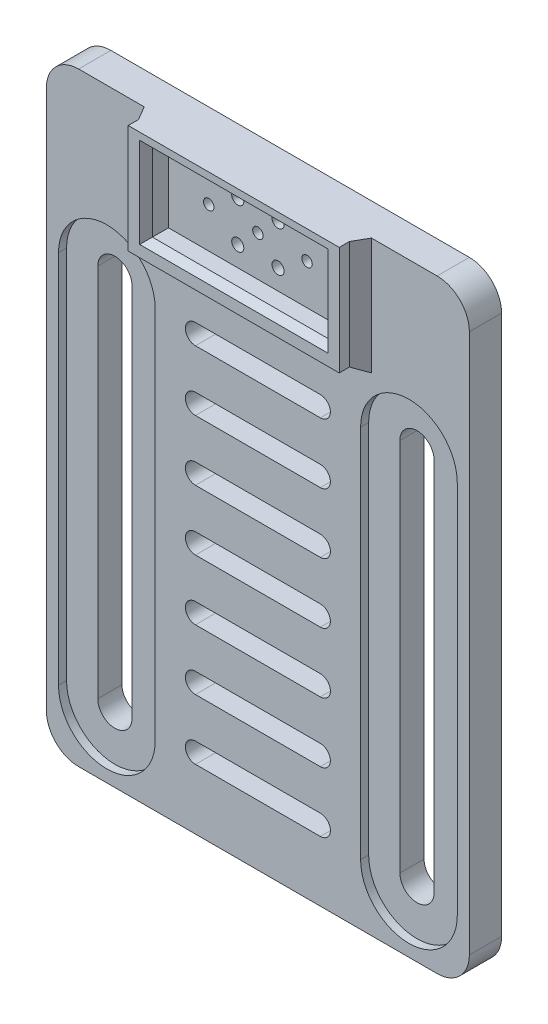
SolidWorks part; units mm, degrees
other "Marca1"
sketch "Croquis5" plane through (0, 0, 14) normal (0, 0, 1) x (1, 0, 0)
sketch "Croquis7" plane through (0, 0, 14) normal (0, 0, 1) x (1, 0, 0)
ref_plane "Alzado" through (0, 0, 0) normal (0, 0, 1) x (1, 0, 0)
ref_plane "Planta" through (0, 0, 0) normal (0, 1, 0) x (1, 0, 0)
ref_plane "Vista lateral" through (0, 0, 0) normal (1, 0, 0) x (0, 0, -1)
sketch "Croquis1" plane through (0, 0, 0) normal (0, 0, 1) x (1, 0, 0)
  line L1 (0, 0) -> (105, 0)
  line L2 (0, 0) -> (0, 150)
  line L3 (0, 150) -> (105, 150)
  line L4 (105, 0) -> (105, 150)
  dimension "D1" = 150
  dimension "D2" = 105
extrude "Saliente-Extruir1" add sketch "Croquis1" along normal blind 8
sketch "Croquis2" plane through (0, 0, 8) normal (0, 0, 1) x (1, 0, 0)
  line L0 (52.5, 150) -> (52.5, 0) construction
  line L1 (105, 150) -> (0, 150) construction
  line L2 (0, 0) -> (105, 0) construction
  line L3 (30, 150) -> (30, 0) construction
  line L4 (80, 150) -> (80, 0) construction
  line L5 (0, 150) -> (0, 0) construction
  line L6 (105, 0) -> (105, 150) construction
  line L7 (30, 150) -> (0, 150) construction
  line L8 (15, 150) -> (15, 0) construction
  line L9 (80, 150) -> (105, 150) construction
  line L10 (92.5, 150) -> (92.5, 0) construction
  line L11 (0, 123) -> (105, 123) construction
  line L12 (15, 108) -> (15, 15) construction
  line L13 (19.25, 108) -> (19.25, 15)
  line L14 (10.75, 108) -> (10.75, 15)
  line L15 (90, 108) -> (90, 15) construction
  line L16 (85.75, 108) -> (85.75, 15)
  line L17 (94.25, 108) -> (94.25, 15)
  line L18 (0, 147) -> (105, 147) construction
  line L19 (0, 127) -> (105, 127) construction
  line L20 (52.5, 147) -> (52.5, 127)
  arc A0 (19.25, 108) -> (10.75, 108) centre (15, 108) ccw
  arc A1 (10.75, 15) -> (19.25, 15) centre (15, 15) ccw
  arc A2 (85.75, 108) -> (94.25, 108) centre (90, 108) cw
  arc A3 (94.25, 15) -> (85.75, 15) centre (90, 15) cw
  circle A4 centre (52.5, 137) radius 1.3
  circle A5 centre (47.5, 142) radius 1.5
  circle A6 centre (47.5, 132) radius 1.5
  circle A7 centre (57.5, 132) radius 1.5
  circle A8 centre (57.5, 142) radius 1.5
  point P26 (15, 61.5)
  point P33 (90, 61.5)
  dimension "D5" = 15
  dimension "D6" = 15
  dimension "D9" = 5
  dimension "D1" = 30
  dimension "D2" = 25
  dimension "D3" = 4
  dimension "D4" = 8.5
  dimension "D7" = 3
  dimension "D8" = 20
  dimension "D10" = 5
  dimension "D11" = 5
  dimension "D12" = 5
extrude "Cortar-Extruir4" cut sketch "Croquis2" against normal up to surface (8 mm away) contours L13 A1 L14 A0 | L17 A3 L16 A2 | A4 | A5 | A6 | A7 | A8 up to face at (52.5, 75, 0)
sketch "Croquis3" plane through (0, 0, 8) normal (0, 0, 1) x (1, 0, 0)
  line L0 (105, 150) -> (0, 150) construction
  line L1 (0, 150) -> (0, 0) construction
  line L2 (105, 0) -> (105, 150) construction
  line L3 (25, 150) -> (0, 150) construction
  line L5 (80.3, 150) -> (106.9126, 150) construction
  line L7 (-0.3, 123) -> (99.7, 123) construction
  line L14 (0, 147) -> (105, 147) construction
  line L15 (2.5, 127) -> (102.5, 127) construction
  line L16 (52.5, 147) -> (52.5, 127)
  line L17 (26.3, 150) -> (26.3, 123)
  line L18 (26.3, 123) -> (78.7, 123)
  line L19 (78.7, 123) -> (78.7, 150)
  line L20 (78.7, 150) -> (26.3, 150)
  line L22 (30.3, 147.1) -> (74.7, 147.1)
  line L23 (30.3, 147.1) -> (30.3, 127)
  line L24 (30.3, 127) -> (74.7, 127)
  line L25 (74.7, 147.1) -> (74.7, 127)
  circle A4 centre (52.5, 137) radius 2.9
  line M26 (105, 150) -> (0, 150)
  dimension "D5" = 4
  dimension "D1" = 4
  dimension "D2" = 4
  dimension "D3" = 20.1
  dimension "D4" = 44.4
  dimension "D6" = 105
  dimension "D7" = 26.3
  dimension "D8" = 26.3
extrude "Saliente-Extruir2" add sketch "Croquis3" along normal blind 6 contours L18 L19 L17 L22 L25 L24 L23 M26
fillet "Redondeo1" radius 8 1 edges at (0, 150, 4)
fillet "Redondeo2" radius 8 1 edges at (105, 150, 4)
fillet "Redondeo3" radius 8 1 edges at (0, 0, 4)
fillet "Redondeo4" radius 8 1 edges at (105, 0, 4)
sketch "Croquis4" plane through (0, 0, 8) normal (0, 0, 1) x (1, 0, 0)
  line L0 (85.75, 108) -> (85.75, 15) construction
  line L1 (94.25, 108) -> (94.25, 15) construction
  line L2 (85.75, 108) -> (85.75, 15)
  line L3 (94.25, 108) -> (94.25, 15)
  line L4 (10.75, 108) -> (10.75, 15) construction
  line L5 (19.25, 108) -> (19.25, 15) construction
  line L6 (10.75, 108) -> (10.75, 15)
  line L7 (19.25, 108) -> (19.25, 15)
  line L8 (15, 108) -> (15, 15) construction
  line L9 (27, 108) -> (27, 15)
  line L10 (3, 108) -> (3, 15)
  line L11 (52.5, 147.1) -> (52.5, 0) construction
  line L14 (30.3, 147.1) -> (74.7, 147.1) construction
  line L15 (8, 0) -> (97, 0) construction
  line L16 (90, 108) -> (90, 15) construction
  line L17 (78, 108) -> (78, 15)
  line L18 (102, 108) -> (102, 15)
  arc A0 (85.75, 15) -> (94.25, 15) centre (90, 15) ccw construction
  arc A1 (94.25, 108) -> (85.75, 108) centre (90, 108) ccw construction
  arc A2 (85.75, 15) -> (94.25, 15) centre (90, 15) ccw
  arc A3 (94.25, 108) -> (85.75, 108) centre (90, 108) ccw
  arc A4 (10.75, 15) -> (19.25, 15) centre (15, 15) ccw construction
  arc A5 (19.25, 108) -> (10.75, 108) centre (15, 108) ccw construction
  arc A6 (10.75, 15) -> (19.25, 15) centre (15, 15) ccw
  arc A7 (19.25, 108) -> (10.75, 108) centre (15, 108) ccw
  arc A8 (27, 108) -> (3, 108) centre (15, 108) ccw
  arc A9 (3, 15) -> (27, 15) centre (15, 15) ccw
  arc A12 (78, 108) -> (102, 108) centre (90, 108) cw
  arc A13 (102, 15) -> (78, 15) centre (90, 15) cw
  point P12 (15, 61.5)
  point P25 (90, 61.5)
  dimension "D1" = 24
extrude "Cortar-Extruir5" cut sketch "Croquis4" against normal blind 2
chamfer "Chaflán1" distance 2 angle 30 4 edges at (52.5, 127, 14) (74.7, 137.05, 14) (30.3, 137.05, 14) (52.5, 147.1, 14)
chamfer "Chaflán2" distance 2 angle 60 3 edges at (26.3, 136.5, 8) (52.5, 123, 8) (78.7, 136.5, 8)
sketch "Croquis6" plane through (0, 0, 8) normal (0, 0, 1) x (1, 0, 0)
  line L0 (37, 17.5) -> (68, 17.5) construction
  line L1 (37, 20) -> (68, 20)
  line L2 (37, 15) -> (68, 15)
  line L3 (78, 108) -> (78, 15) construction
  line L4 (27, 15) -> (27, 108) construction
  line L5 (37, 30) -> (68, 30)
  line L6 (37, 35) -> (68, 35)
  line L7 (37, 32.5) -> (68, 32.5) construction
  line L8 (37, 45) -> (68, 45)
  line L9 (37, 50) -> (68, 50)
  line L10 (37, 47.5) -> (68, 47.5) construction
  line L11 (37, 60) -> (68, 60)
  line L12 (37, 65) -> (68, 65)
  line L13 (37, 62.5) -> (68, 62.5) construction
  line L14 (37, 75) -> (68, 75)
  line L15 (37, 80) -> (68, 80)
  line L16 (37, 77.5) -> (68, 77.5) construction
  line L17 (37, 90) -> (68, 90)
  line L18 (37, 95) -> (68, 95)
  line L19 (37, 92.5) -> (68, 92.5) construction
  line L20 (37, 105) -> (68, 105)
  line L21 (37, 110) -> (68, 110)
  line L22 (37, 107.5) -> (68, 107.5) construction
  arc A0 (37, 20) -> (37, 15) centre (37, 17.5) ccw
  arc A1 (68, 15) -> (68, 20) centre (68, 17.5) ccw
  arc A2 (10.75, 15) -> (19.25, 15) centre (15, 15) ccw construction
  arc A3 (37, 35) -> (37, 30) centre (37, 32.5) ccw
  arc A4 (68, 30) -> (68, 35) centre (68, 32.5) ccw
  arc A5 (37, 50) -> (37, 45) centre (37, 47.5) ccw
  arc A6 (68, 45) -> (68, 50) centre (68, 47.5) ccw
  arc A7 (37, 65) -> (37, 60) centre (37, 62.5) ccw
  arc A8 (68, 60) -> (68, 65) centre (68, 62.5) ccw
  arc A9 (37, 80) -> (37, 75) centre (37, 77.5) ccw
  arc A10 (68, 75) -> (68, 80) centre (68, 77.5) ccw
  arc A11 (37, 95) -> (37, 90) centre (37, 92.5) ccw
  arc A12 (68, 90) -> (68, 95) centre (68, 92.5) ccw
  arc A13 (37, 110) -> (37, 105) centre (37, 107.5) ccw
  arc A14 (68, 105) -> (68, 110) centre (68, 107.5) ccw
  point P2 (52.5, 17.5)
  point P18 (52.5, 32.5)
  point P25 (52.5, 47.5)
  point P32 (52.5, 62.5)
  point P39 (52.5, 77.5)
  point P46 (52.5, 92.5)
  point P53 (52.5, 107.5)
  dimension "D1" = 10
  dimension "D2" = 10
  dimension "D4" = 0
  dimension "D3" = 5
  dimension "D6" = 10
  dimension "D5" = 7
extrude "Cortar-Extruir6" cut sketch "Croquis6" against normal up to surface (8 mm away) up to face at (46, 132, 0)
sketch "Croquis8" plane through (0, 0, 0) normal (0, 0, -1) x (-1, 0, 0)
  line L1 (-52.5, 140.1754) -> (-55.25, 138.5877)
  line L2 (-55.25, 138.5877) -> (-55.25, 135.4123)
  line L3 (-55.25, 135.4123) -> (-52.5, 133.8246)
  line L4 (-52.5, 133.8246) -> (-49.75, 135.4123)
  line L5 (-49.75, 135.4123) -> (-49.75, 138.5877)
  line L6 (-49.75, 138.5877) -> (-52.5, 140.1754)
  line L12 (-52.5, 147.1) -> (-52.5, 127) construction
  line L13 (-52.5, 137) -> (-74.7, 137.05) construction
  line L14 (-64.7, 140.2029) -> (-67.45, 138.6152)
  line L15 (-67.45, 135.4398) -> (-64.7, 133.8521)
  line L16 (-30.3, 147.1) -> (-74.7, 147.1)
  line L17 (-30.3, 127) -> (-30.3, 147.1)
  line L18 (-74.7, 127) -> (-30.3, 127)
  line L19 (-74.7, 147.1) -> (-74.7, 127)
  line L20 (-30.3, 147.1) -> (-74.7, 147.1)
  line L21 (-30.3, 127) -> (-30.3, 147.1)
  line L22 (-74.7, 127) -> (-30.3, 127)
  line L23 (-74.7, 147.1) -> (-74.7, 127)
  line L24 (-61.95, 138.6152) -> (-64.7, 140.2029)
  line L25 (-61.95, 135.4398) -> (-61.95, 138.6152)
  line L26 (-67.45, 138.6152) -> (-67.45, 135.4398)
  line L27 (-64.7, 133.8521) -> (-61.95, 135.4398)
  line L28 (-37.55, 138.6152) -> (-40.3, 140.2029)
  line L29 (-40.3, 133.8521) -> (-37.55, 135.4398)
  line L30 (-37.55, 135.4398) -> (-37.55, 138.6152)
  line L31 (-40.3, 140.2029) -> (-43.05, 138.6152)
  line L32 (-43.05, 135.4398) -> (-40.3, 133.8521)
  line L33 (-43.05, 138.6152) -> (-43.05, 135.4398)
  circle A0 centre (-52.5, 137) radius 1.3 construction
  circle A1 centre (-52.5, 137) radius 1.3
  circle A2 centre (-52.5, 137) radius 2.75 construction
  circle A3 centre (-64.7, 137.0275) radius 1.3
  circle A4 centre (-40.3, 137.0275) radius 1.3
  circle M33 centre (-52.5, 137) radius 1.3
  dimension "D3" = 10
  dimension "D1" = 5.5
  dimension "D2" = 0
extrude "Cortar-Extruir7" cut sketch "Croquis8" against normal blind 2.45 contours L15 L27 L25 L24 L14 L26 A3 | L5 L6 L1 L2 L3 L4 M33 | L31 L33 L32 L29 L30 L28 A4 | A4 | A1
chamfer "Chaflán3" distance 0.5 angle 60 18 edges at (55.25, 137, 0) (53.875, 139.3816, 0) (51.125, 139.3816, 0) (49.75, 137, 0) (51.125, 134.6184, 0) (53.875, 134.6184, 0) (38.925, 134.6459, 0) (37.55, 137.0275, 0) (38.925, 139.409, 0) (41.675, 139.409, 0) (43.05, 137.0275, 0) (41.675, 134.6459, 0) (66.075, 139.409, 0) (67.45, 137.0275, 0) (66.075, 134.6459, 0) (61.95, 137.0275, 0) (63.325, 134.6459, 0) (63.325, 139.409, 0)
sketch "Croquis9" plane through (0, 0, 0) normal (0, 0, -1) x (-1, 0, 0)
  line L0 (-52.5, 140.7528) -> (-52.5, 133.2472) construction
  line L1 (-67.45, 137.0275) -> (-61.95, 137.0275) construction
  line L6 (-67.45, 135.4398) -> (-64.7, 133.8521)
  line L7 (-64.7, 133.8521) -> (-61.95, 135.4398)
  line L8 (-61.95, 135.4398) -> (-61.95, 138.6152)
  line L9 (-61.95, 138.6152) -> (-64.7, 140.2029)
  line L10 (-64.7, 140.2029) -> (-67.45, 138.6152)
  line L11 (-67.45, 138.6152) -> (-67.45, 135.4398)
  line L12 (-67.45, 135.4398) -> (-64.7, 133.8521)
  line L13 (-64.7, 133.8521) -> (-61.95, 135.4398)
  line L14 (-61.95, 135.4398) -> (-61.95, 138.6152)
  line L16 (-64.7, 140.2029) -> (-67.45, 138.6152)
  line L17 (-67.45, 138.6152) -> (-67.45, 135.4398)
  line L21 (-61.95, 138.6152) -> (-64.7, 140.2029)
  circle A0 centre (-64.7, 137.0275) radius 1.3
  circle A1 centre (-40.3, 137.0275) radius 1.3
  dimension "D1" = 0
extrude "Cortar-Extruir9" cut sketch "Croquis9" against normal up to surface (8 mm away) contours A0 | A1 up to face at (49, 132, 8)
